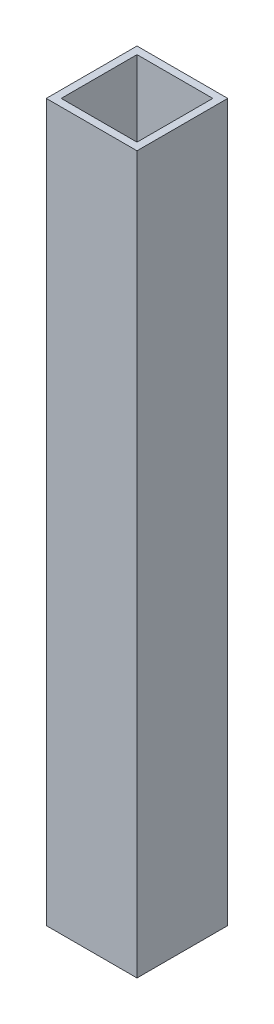
SolidWorks part; units mm, degrees
ref_plane "Front Plane" through (0, 0, 0) normal (0, 0, 1) x (1, 0, 0)
ref_plane "Top Plane" through (0, 0, 0) normal (0, 1, 0) x (1, 0, 0)
ref_plane "Right Plane" through (0, 0, 0) normal (1, 0, 0) x (0, 0, -1)
sketch "Sketch1" plane through (0, 0, 0) normal (0, 1, 0) x (1, 0, 0)
  line L0 (-8.0645, 8.0645) -> (8.0645, 8.0645)
  line L1 (-9.652, 9.652) -> (9.652, 9.652)
  line L2 (-9.652, 9.652) -> (-9.652, -9.652)
  line L3 (-9.652, -9.652) -> (9.652, -9.652)
  line L4 (9.652, 9.652) -> (9.652, -9.652)
  line L5 (-9.652, 9.652) -> (9.652, -9.652) construction
  line L6 (-9.652, -9.652) -> (9.652, 9.652) construction
  line L7 (8.0645, 8.0645) -> (8.0645, -8.0645)
  line L8 (-8.0645, -8.0645) -> (8.0645, -8.0645)
  line L9 (-8.0645, 8.0645) -> (-8.0645, -8.0645)
  point P0 (0, 0)
  dimension "D1" = 19.304
  dimension "D2" = 1.5875
extrude "Boss-Extrude1" add sketch "Sketch1" along normal mid plane 152.4
